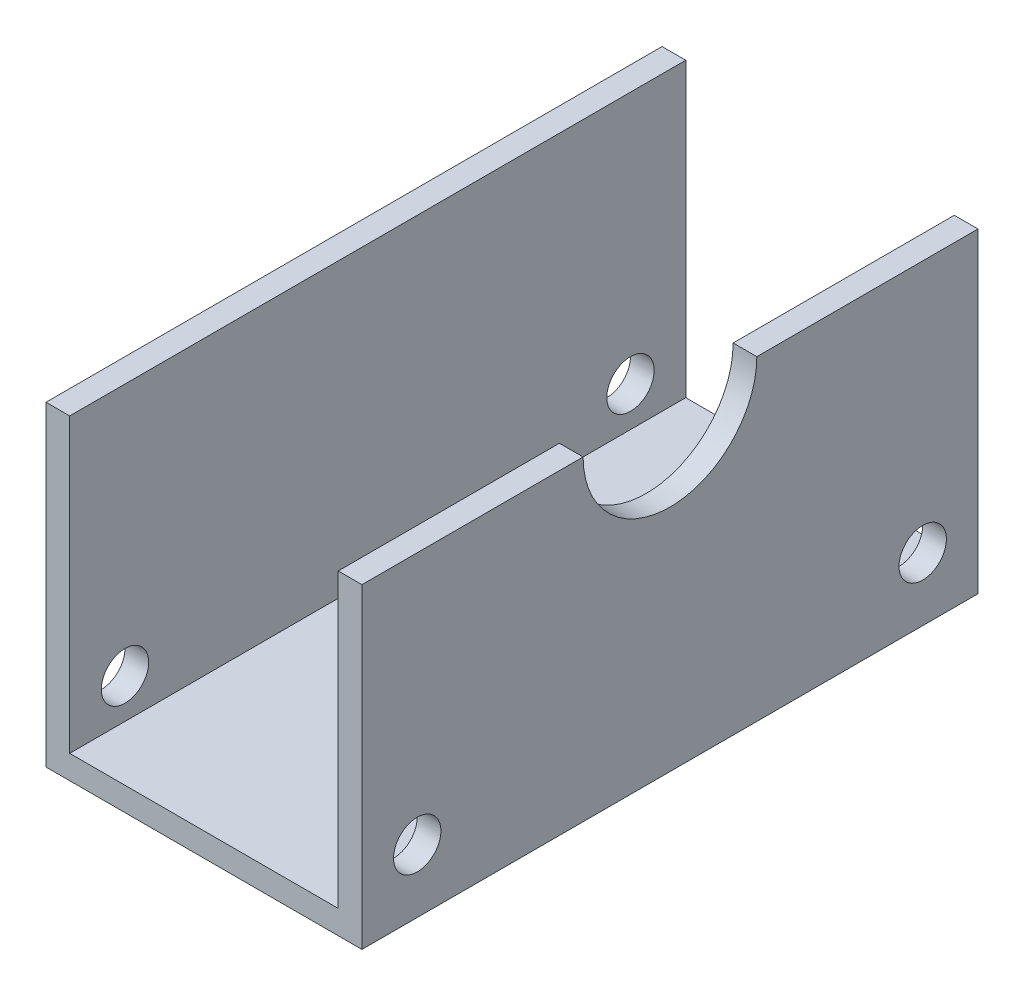
SolidWorks part; units mm, degrees
ref_plane "Plan de face" through (0, 0, 0) normal (0, 0, 1) x (1, 0, 0)
ref_plane "Plan de dessus" through (0, 0, 0) normal (0, 1, 0) x (1, 0, 0)
ref_plane "Plan de droite" through (0, 0, 0) normal (1, 0, 0) x (0, 0, -1)
sketch "Esquisse1" plane through (0, 0, 0) normal (0, 0, 1) x (1, 0, 0)
  line L0 (-16.6363, 16.5902) -> (-16.6363, -3.4098)
  line L1 (-16.6363, -3.4098) -> (3.3637, -3.4098)
  line L2 (3.3637, -3.4098) -> (3.3637, 16.5902)
  line L3 (3.3637, 16.5902) -> (1.8637, 16.5902)
  line L4 (1.8637, 16.5902) -> (1.8637, -1.9098)
  line L5 (1.8637, -1.9098) -> (-15.1363, -1.9098)
  line L6 (-15.1363, -1.9098) -> (-15.1363, 16.5902)
  line L7 (-15.1363, 16.5902) -> (-16.6363, 16.5902)
  dimension "D1" = 1.5
  dimension "D2" = 1.5
  dimension "D3" = 1.5
  dimension "D4" = 20
  dimension "D5" = 20
  dimension "D6" = 20
extrude "Extrusion1" add sketch "Esquisse1" along normal blind 39
sketch "Esquisse2" plane through (3.3637, 0, 0) normal (1, 0, 0) x (0, 0, -1)
  line L0 (-39, 16.5902) -> (0, 16.5902) construction
  circle A0 centre (-19.5, 16.5902) radius 5.5
extrude "Extrusion2" cut sketch "Esquisse2" against normal blind 10
sketch "Esquisse3" plane through (-16.6363, 0, 0) normal (-1, 0, 0) x (0, 0, 1)
  line L0 (39, -3.4098) -> (0, -3.4098) construction
  line L3 (0, 16.5902) -> (0, -3.4098) construction
  line L4 (39, 16.5902) -> (39, -3.4098) construction
  circle A0 centre (3.5, 0.5902) radius 1.5
  circle A1 centre (35.5, 0.5902) radius 1.5
  dimension "D1" = 4
  dimension "D4" = 4
  dimension "D2" = 3.5
  dimension "D3" = 3.5
extrude "Extrusion3" cut sketch "Esquisse3" against normal through all
